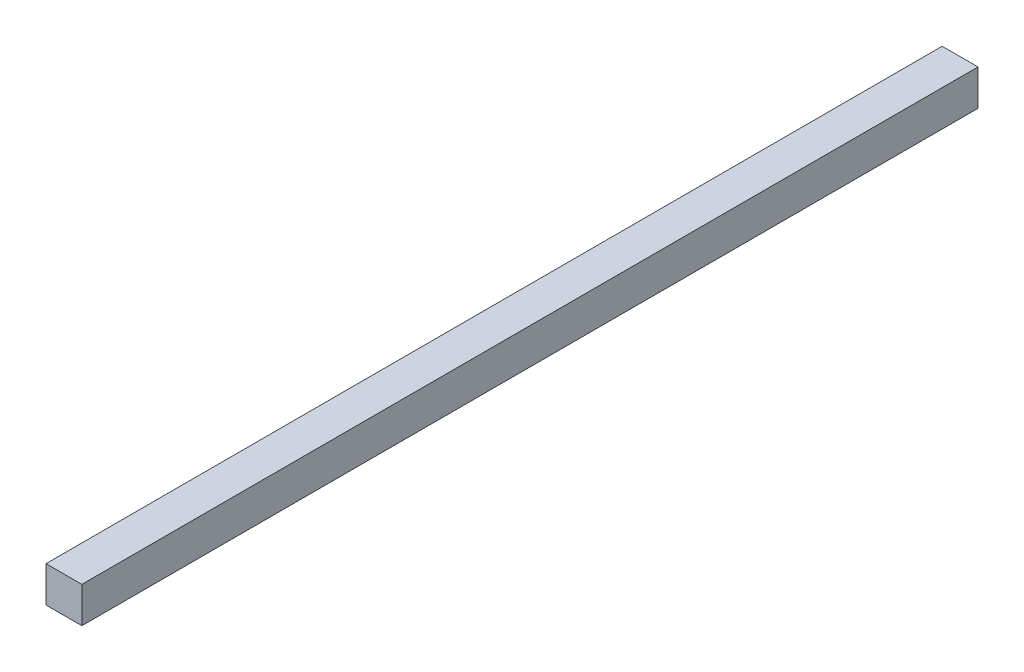
SolidWorks part; units mm, degrees
ref_plane "Front Plane" through (0, 0, 0) normal (0, 0, 1) x (1, 0, 0)
ref_plane "Top Plane" through (0, 0, 0) normal (0, 1, 0) x (1, 0, 0)
ref_plane "Right Plane" through (0, 0, 0) normal (1, 0, 0) x (0, 0, -1)
sketch "Sketch1" plane through (0, 0, 0) normal (0, 0, 1) x (1, 0, 0)
  line L1 (-10, 10) -> (10, 10)
  line L2 (-10, 10) -> (-10, -10)
  line L3 (-10, -10) -> (10, -10)
  line L4 (10, 10) -> (10, -10)
  line L5 (-10, 10) -> (10, -10) construction
  line L6 (-10, -10) -> (10, 10) construction
  point P0 (0, 0)
  dimension "D1" = 20
  dimension "D2" = 20
extrude "Boss-Extrude1" add sketch "Sketch1" along normal blind 500
